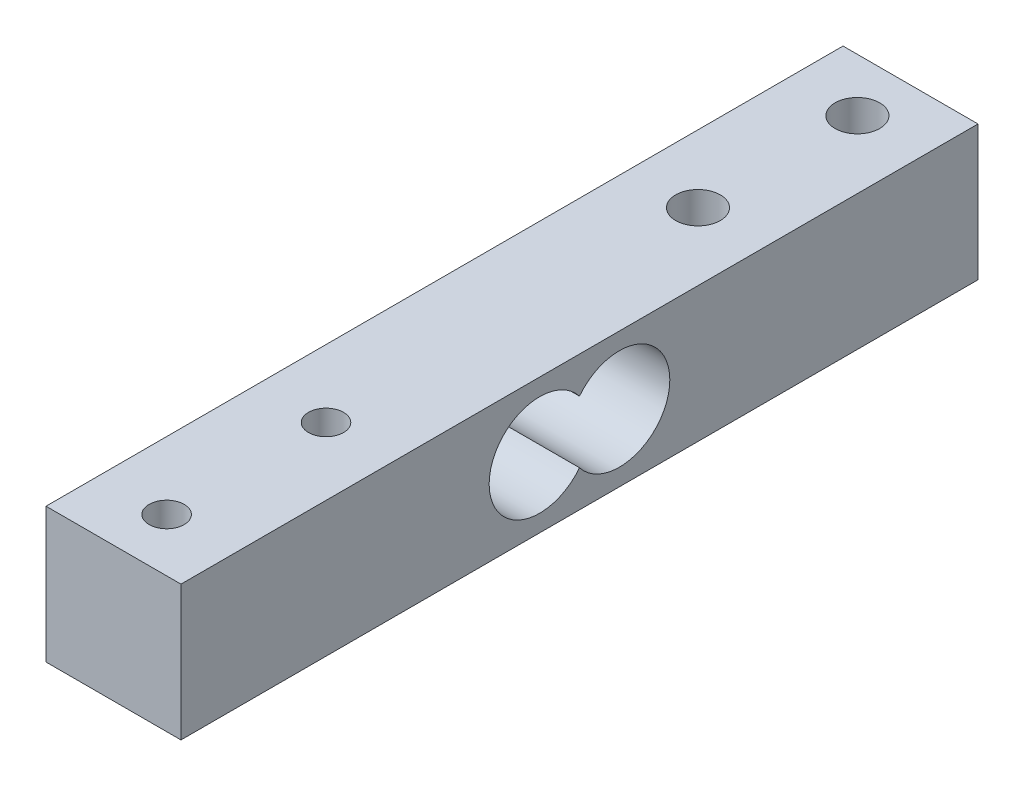
SolidWorks part; units mm, degrees
ref_plane "Front Plane" through (0, 0, 0) normal (0, 0, 1) x (1, 0, 0)
ref_plane "Top Plane" through (0, 0, 0) normal (0, 1, 0) x (1, 0, 0)
ref_plane "Right Plane" through (0, 0, 0) normal (1, 0, 0) x (0, 0, -1)
sketch "Sketch1" plane through (0, 0, 0) normal (0, 1, 0) x (1, 0, 0)
  line L1 (-6.35, 37.5) -> (6.35, 37.5)
  line L2 (-6.35, 37.5) -> (-6.35, -37.5)
  line L3 (-6.35, -37.5) -> (6.35, -37.5)
  line L4 (6.35, 37.5) -> (6.35, -37.5)
  line L5 (-6.35, 37.5) -> (6.35, -37.5) construction
  line L6 (-6.35, -37.5) -> (6.35, 37.5) construction
  point P0 (0, 0)
  dimension "D1" = 12.7
  dimension "D2" = 75
extrude "Boss-Extrude1" add sketch "Sketch1" along normal mid plane 12.7
sketch "Sketch2" plane through (0, 6.35, 0) normal (0, 1, 0) x (1, 0, 0)
  line L1 (0, -17.5) -> (0, -32.5) construction
  line L2 (0, 0) -> (-50000, 0) construction
  line L4 (-6.35, -37.5) -> (6.35, -37.5) construction
  point P6 (0, -25)
  point P7 (0, -17.5)
  point P8 (0, -32.5)
  dimension "D1" = 15
  dimension "D2" = 5
hole_wizard "Tap Drill for M4x0.7 Tap1" positions "Sketch2" profile "Sketch3" hole size "M4x0.7" standard "ANSI Metric"
sketch "Sketch3" plane through (0, 6.35, 32.5) normal (1, 0, 0) x (0, 0, 1)
  line L0 (0, 0) -> (0, 12.7)
  line L1 (0, 12.7) -> (1.65, 12.7)
  line L2 (1.65, 12.7) -> (1.65, 0)
  line L5 (1.65, 0) -> (0, 0)
  line L11 (0, -6.35) -> (0, 107.95) construction
  dimension "Thru Hole Dia." = 3.3
  dimension "Thru Hole Depth" = 12.7
sketch "Sketch7" plane through (-6.35, 0, 0) normal (-1, 0, 0) x (0, 0, 1)
  line L0 (-3.75, 0) -> (3.75, 0) construction
  circle A0 centre (-3.75, 0) radius 4.75
  circle A1 centre (3.75, 0) radius 4.75
  point P8 (0, 0)
  dimension "D1" = 9.5
  dimension "D2" = 7.5
extrude "Cut-Extrude1" cut sketch "Sketch7" against normal through all
sketch "Sketch8" plane through (0, 6.35, 0) normal (0, 1, 0) x (1, 0, 0)
  line L0 (0, 32.5) -> (0, 17.5) construction
  line L1 (6.35, 37.5) -> (-6.35, 37.5) construction
  point P4 (0, 25)
  point P5 (0, 32.5)
  point P6 (0, 17.5)
  dimension "D1" = 15
  dimension "D2" = 5
hole_wizard "Tap Drill for M5x0.8 Tap1" positions "Sketch8" profile "Sketch9" hole size "M5x0.8" standard "ANSI Metric"
sketch "Sketch9" plane through (0, 6.35, -17.5) normal (1, 0, 0) x (0, 0, 1)
  line L0 (0, 0) -> (0, 16.2618)
  line L1 (0, 16.2618) -> (2.1, 15)
  line L2 (2.1, 15) -> (2.1, 0)
  line L5 (2.1, 0) -> (0, 0)
  line L10 (0, 16.2618) -> (-2.1, 15) construction
  line L11 (0, -6.35) -> (0, 107.95) construction
  dimension "Hole Dia." = 4.2
  dimension "Hole Depth" = 15
  dimension "Drill Angle" = 118
